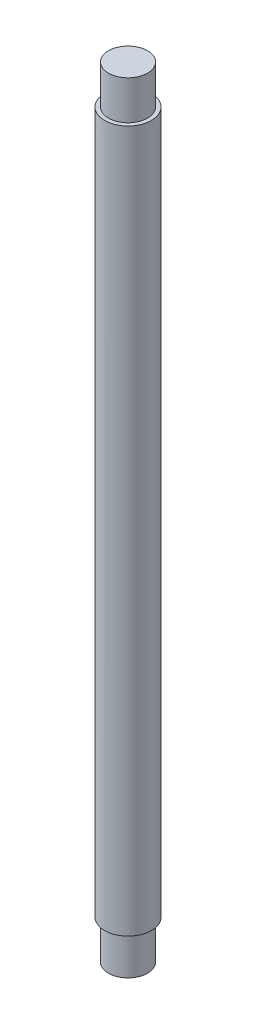
SolidWorks part; units mm, degrees
material "Plain Carbon Steel"
ref_plane "Front Plane" through (0, 0, 0) normal (0, 0, 1) x (1, 0, 0)
ref_plane "Top Plane" through (0, 0, 0) normal (0, 1, 0) x (1, 0, 0)
ref_plane "Right Plane" through (0, 0, 0) normal (1, 0, 0) x (0, 0, -1)
sketch "Sketch1" plane through (0, 0, 0) normal (0, 1, 0) x (1, 0, 0)
  circle A0 centre (0, 0) radius 3
extrude "Boss-Extrude1" add sketch "Sketch1" along normal blind 100
sketch "Sketch2" plane through (0, 0, 0) normal (0, -1, 0) x (1, 0, 0)
  circle A0 centre (0, 0) radius 2.5
  circle A1 centre (0, 0) radius 3.8047
extrude "Cut-Extrude1" cut sketch "Sketch2" against normal blind 5
sketch "Sketch3" plane through (0, 100, 0) normal (0, 1, 0) x (1, 0, 0)
  circle A0 centre (0, 0) radius 2.5
  circle A1 centre (0, 0) radius 4.6343
extrude "Cut-Extrude2" cut sketch "Sketch3" against normal blind 5
